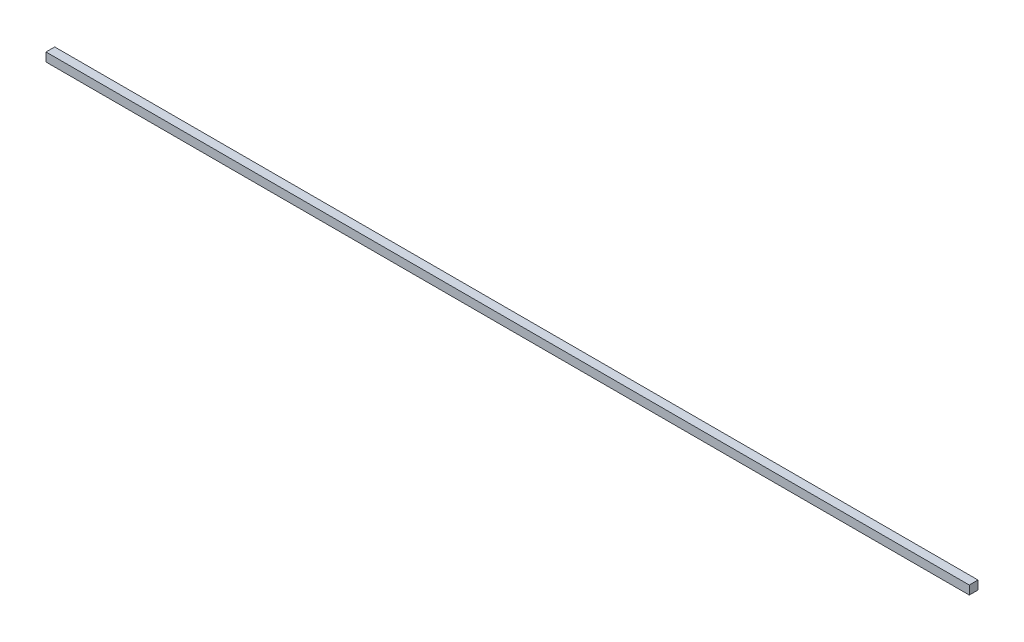
SolidWorks part; units mm, degrees
material "Balsa"
ref_plane "Front Plane" through (0, 0, 0) normal (0, 0, 1) x (1, 0, 0)
ref_plane "Top Plane" through (0, 0, 0) normal (0, 1, 0) x (1, 0, 0)
ref_plane "Right Plane" through (0, 0, 0) normal (1, 0, 0) x (0, 0, -1)
sketch "Sketch1" plane through (0, 0, 0) normal (0, 1, 0) x (1, 0, 0)
  line L1 (-336.55, -3.175) -> (336.55, -3.175)
  line L2 (-336.55, -3.175) -> (-336.55, 3.175)
  line L3 (-336.55, 3.175) -> (336.55, 3.175)
  line L4 (336.55, -3.175) -> (336.55, 3.175)
  line L5 (-336.55, -3.175) -> (336.55, 3.175) construction
  line L6 (-336.55, 3.175) -> (336.55, -3.175) construction
  point P0 (0, 0)
  dimension "D1" = 6.35
  dimension "D2" = 673.1
extrude "Boss-Extrude2" add sketch "Sketch1" along normal blind 6.35
